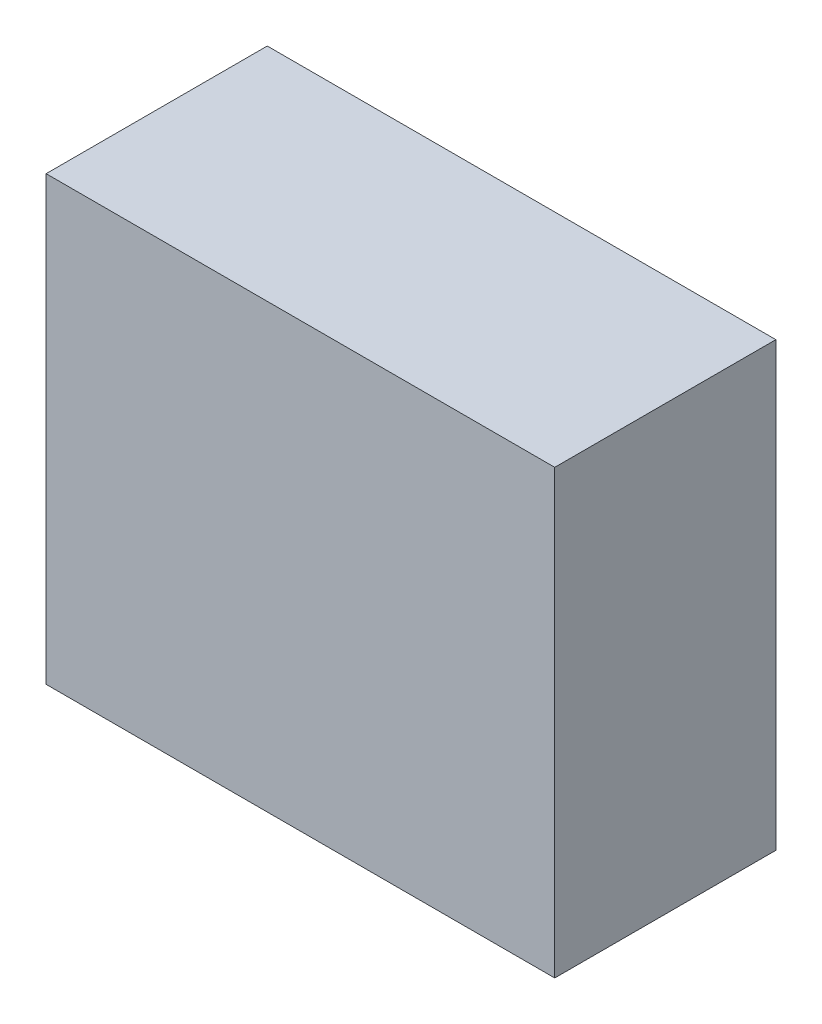
SolidWorks part; units mm, degrees
ref_plane "Front Plane" through (0, 0, 0) normal (0, 0, 1) x (1, 0, 0)
ref_plane "Top Plane" through (0, 0, 0) normal (0, 1, 0) x (1, 0, 0)
ref_plane "Right Plane" through (0, 0, 0) normal (1, 0, 0) x (0, 0, -1)
sketch "Sketch1" plane through (0, 0, 0) normal (0, 0, 1) x (1, 0, 0)
  line L1 (0, 0) -> (23, 0)
  line L2 (0, 0) -> (0, 20)
  line L3 (0, 20) -> (23, 20)
  line L4 (23, 0) -> (23, 20)
extrude "Boss-Extrude1" add sketch "Sketch1" along normal blind 10
